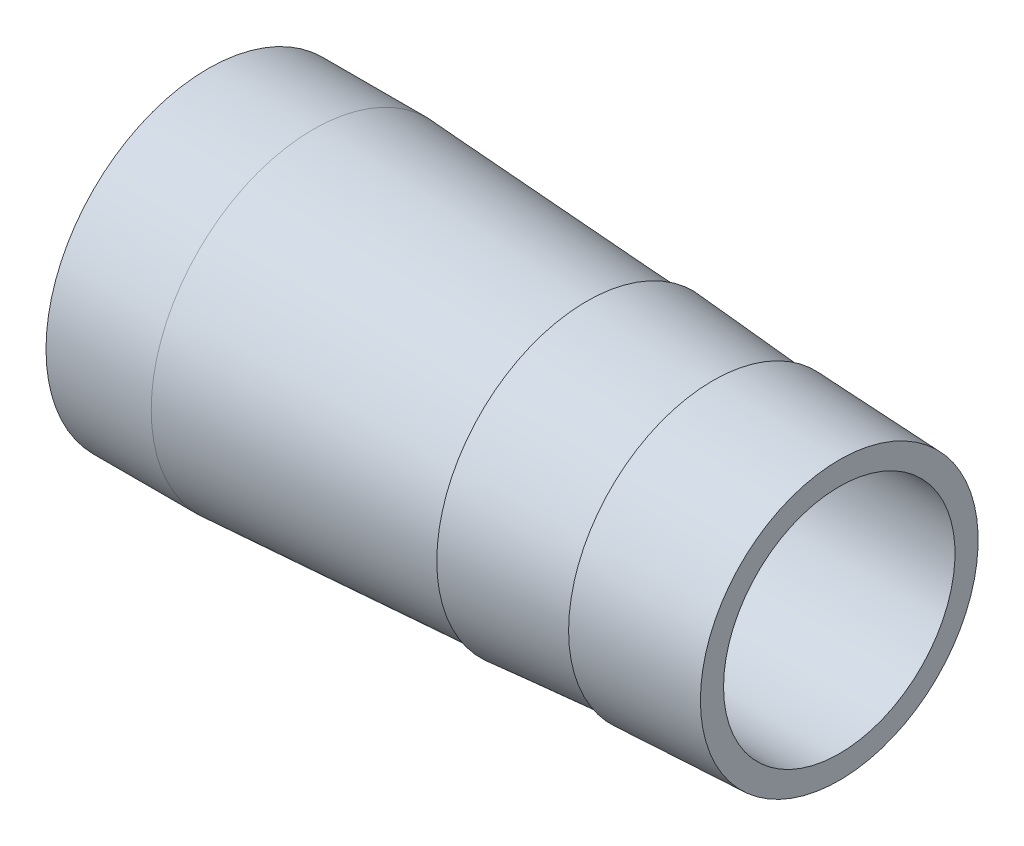
SolidWorks part; units mm, degrees
ref_plane "Front Plane" through (0, 0, 0) normal (0, 0, 1) x (1, 0, 0)
ref_plane "Top Plane" through (0, 0, 0) normal (0, 1, 0) x (1, 0, 0)
ref_plane "Right Plane" through (0, 0, 0) normal (1, 0, 0) x (0, 0, -1)
sketch "Sketch1" plane through (0, 0, 0) normal (0, 0, 1) x (1, 0, 0)
  line L0 (-17.9943, 0) -> (23.8363, 0) construction
  line L1 (7.0257, 6.864) -> (13.0257, 6.6)
  line L3 (-16.9743, 5.5) -> (-11.9743, 5.5)
  line L5 (-11.9743, 5.5) -> (13.0257, 5.5)
  line L6 (-16.9743, 5.5) -> (-16.9743, 7.7)
  line L7 (-16.9743, 7.7) -> (-11.9743, 7.7)
  line L9 (13.0257, 6.6) -> (13.0257, 5.5)
  line L10 (7.0257, 6.864) -> (7.0257, 6.6637)
  line L11 (7.0257, 6.6637) -> (1.0257, 7.128)
  line L12 (1.0257, 7.128) -> (1.0257, 6.933)
  line L13 (1.0257, 6.933) -> (-11.9743, 7.7)
  dimension "D1" = 5.5
  dimension "D2" = 6.6
  dimension "D3" = 5.5
  dimension "D4" = 7.7
  dimension "D5" = 30
revolve "Revolve1" add sketch "Sketch1" angle 360 about L0
